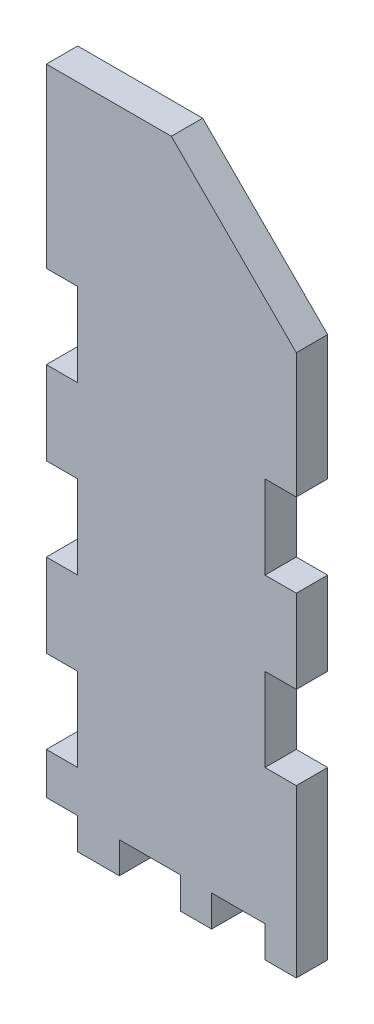
SolidWorks part; units mm, degrees
ref_plane "Front Plane" through (0, 0, 0) normal (0, 0, 1) x (1, 0, 0)
ref_plane "Top Plane" through (0, 0, 0) normal (0, 1, 0) x (1, 0, 0)
ref_plane "Right Plane" through (0, 0, 0) normal (1, 0, 0) x (0, 0, -1)
sketch "Sketch2" plane through (0, 0, 0) normal (0, 0, 1) x (1, 0, 0)
  line L0 (0, 0) -> (38.1, 0)
  line L1 (0, 0) -> (0, 101.6)
  line L2 (0, 101.6) -> (19.05, 101.6)
  line L3 (19.05, 101.6) -> (38.1, 82.55)
  line L4 (38.1, 82.55) -> (38.1, 0)
  dimension "D1" = 101.6
  dimension "D2" = 38.1
  dimension "D3" = 19.05
  dimension "D4" = 82.55
extrude "Boss-Extrude1" add sketch "Sketch2" along normal blind 4.7752
sketch "Sketch3" plane through (0, 0, 4.7752) normal (0, 0, 1) x (1, 0, 0)
  line L0 (0, 0) -> (0, 4.7752) construction
  line L1 (0, 101.6) -> (0, 0) construction
  line L2 (0, 4.7752) -> (38.1, 4.7752) construction
  line L3 (38.1, 0) -> (38.1, 82.55) construction
  line L4 (0, 0) -> (4.7752, 0) construction
  line L5 (0, 0) -> (38.1, 0) construction
  line L6 (11.1252, 0) -> (20.4174, 0)
  line L7 (4.7752, 0) -> (11.1252, 0)
  line L8 (4.7752, 0) -> (4.7752, 4.7752)
  line L9 (4.7752, 4.7752) -> (11.1252, 4.7752)
  line L10 (11.1252, 0) -> (11.1252, 4.7752)
  line L12 (20.4174, 0) -> (25.1926, 0)
  line L13 (20.4174, 0) -> (20.4174, 4.7752)
  line L14 (20.4174, 4.7752) -> (25.1926, 4.7752)
  line L15 (25.1926, 0) -> (25.1926, 4.7752)
  line L16 (38.1, 0) -> (33.3248, 0)
  line L17 (38.1, 0) -> (38.1, 4.7752)
  line L18 (38.1, 4.7752) -> (33.3248, 4.7752)
  line L19 (33.3248, 0) -> (33.3248, 4.7752)
  line L20 (11.1252, 4.7752) -> (20.4174, 4.7752)
  line L21 (11.1252, 4.7752) -> (11.1252, 0)
  line L22 (11.1252, 0) -> (20.4174, 0)
  line L23 (20.4174, 4.7752) -> (20.4174, 0)
  line L24 (25.1926, 4.7752) -> (33.3248, 4.7752)
  line L25 (25.1926, 4.7752) -> (25.1926, 0)
  line L26 (25.1926, 0) -> (33.3248, 0)
  line L27 (33.3248, 4.7752) -> (33.3248, 0)
  line L28 (0, 4.7752) -> (4.7752, 4.7752)
  line L29 (0, 4.7752) -> (0, 0)
  line L30 (0, 0) -> (4.7752, 0)
  line L31 (4.7752, 4.7752) -> (4.7752, 0)
  line M2 (0, 101.6) -> (0, 0)
  line M3 (0, 0) -> (38.1, 0)
  dimension "D1" = 4.7752
  dimension "D2" = 6.35
  dimension "D3" = 4.7752
  dimension "D4" = 4.7752
  dimension "D5" = 4.7752
  dimension "D6" = 8.1322
extrude "Cut-Extrude2" cut sketch "Sketch3" against normal blind 6.35 contours L28 L8 M2 M3 | L20 L10 L13 M3 | L24 L15 L19 M3
sketch "Sketch5" plane through (0, 0, 4.7752) normal (0, 0, 1) x (1, 0, 0)
  line L0 (38.1, 0) -> (38.1, 82.55) construction
  point P2 (38.1, 41.275)
sketch "Sketch6" plane through (0, 0, 4.7752) normal (0, 0, 1) x (1, 0, 0)
  line L0 (0, 101.6) -> (0, 4.7752) construction
  line L5 (4.7752, 11.1252) -> (0, 11.1252)
  line L6 (4.7752, 11.1252) -> (4.7752, 23.8252)
  line L7 (4.7752, 23.8252) -> (0, 23.8252)
  line L8 (0, 11.1252) -> (0, 23.8252)
  line L9 (38.1, 0) -> (38.1, 82.55) construction
  line L14 (4.7752, 36.5252) -> (0, 36.5252)
  line L15 (4.7752, 36.5252) -> (4.7752, 49.2252)
  line L16 (4.7752, 49.2252) -> (0, 49.2252)
  line L17 (0, 36.5252) -> (0, 49.2252)
  line L22 (0, 61.9252) -> (4.7752, 61.9252)
  line L23 (0, 61.9252) -> (0, 74.6252)
  line L24 (0, 74.6252) -> (4.7752, 74.6252)
  line L25 (4.7752, 61.9252) -> (4.7752, 74.6252)
  line L30 (38.1, 63.5) -> (33.3248, 63.5)
  line L31 (38.1, 63.5) -> (38.1, 50.8)
  line L32 (38.1, 50.8) -> (33.3248, 50.8)
  line L33 (33.3248, 63.5) -> (33.3248, 50.8)
  line L35 (33.3248, 38.1) -> (38.1, 38.1)
  line L36 (33.3248, 38.1) -> (33.3248, 25.4)
  line L37 (33.3248, 25.4) -> (38.1, 25.4)
  line L38 (38.1, 38.1) -> (38.1, 25.4)
  line L39 (19.05, 101.6) -> (0, 101.6) construction
  dimension "D1" = 4.7752
  dimension "D2" = 4.7752
  dimension "D3" = 12.7
  dimension "D4" = 12.7
  dimension "D5" = 12.7
  dimension "D6" = 12.7
  dimension "D7" = 12.7
  dimension "D8" = 4.7752
  dimension "D9" = 12.7
  dimension "D10" = 4.7752
  dimension "D11" = 4.7752
  dimension "D12" = 26.9748
extrude "Cut-Extrude3" cut sketch "Sketch6" against normal blind 6.35 contours L23 L22 L25 L24 | L31 L30 L33 L32 | L15 L14 L17 L16 | L36 L35 L38 L37 | L6 L5 L8 L7
